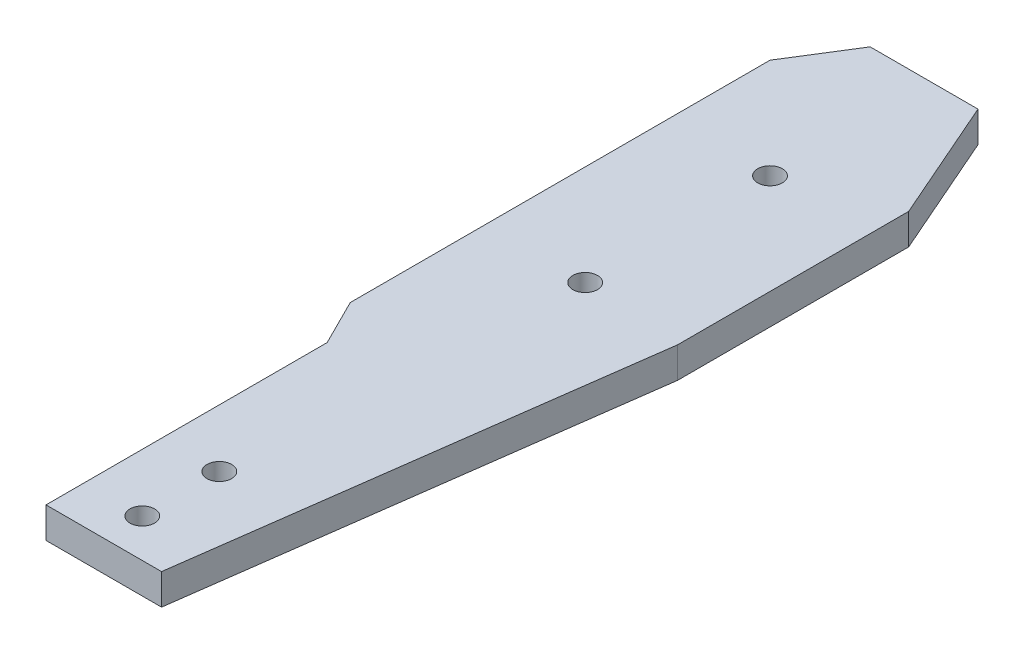
SolidWorks part; units mm, degrees
ref_plane "Front Plane" through (0, 0, 0) normal (0, 0, 1) x (1, 0, 0)
ref_plane "Top Plane" through (0, 0, 0) normal (0, 1, 0) x (1, 0, 0)
ref_plane "Right Plane" through (0, 0, 0) normal (1, 0, 0) x (0, 0, -1)
sketch "Sketch1" plane through (0, 0, 0) normal (0, 1, 0) x (1, 0, 0)
  line L1 (0, -54.5) -> (-3, -60.5)
  line L2 (-3, -60.5) -> (-3, -97)
  line L3 (-3, -97) -> (-18, -97)
  line L4 (-18, -97) -> (-26, -38)
  line L5 (-26, -38) -> (-26, -8)
  line L6 (-26, -8) -> (-19, 8)
  line L7 (-19, 8) -> (-5, 8)
  line L8 (-5, 8) -> (0, 0)
  line L10 (0, 0) -> (0, -54.5)
  line L11 (5, 8) -> (0, 0)
  line L12 (19, 8) -> (5, 8)
  line L13 (26, -8) -> (19, 8)
  line L14 (26, -38) -> (26, -8)
  line L15 (18, -97) -> (26, -38)
  line L16 (3, -97) -> (18, -97)
  line L17 (3, -60.5) -> (3, -97)
  line L18 (0, -54.5) -> (3, -60.5)
  dimension "D2" = 105
  dimension "D3" = 6
  dimension "D4" = 3
  dimension "D5" = 15
  dimension "D6" = 30
  dimension "D7" = 16
  dimension "D8" = 14
  dimension "D9" = 8
  dimension "D10" = 5
  dimension "D11" = 36.5
  dimension "D12" = 26
extrude "Boss-Extrude1" add sketch "Sketch1" along normal blind 4 contours L10 L18 L17 L16 L15 L14 L13 L12 L11
sketch "Sketch2" plane through (0, 4, 0) normal (0, 1, 0) x (1, 0, 0)
  line L4 (0, 0) -> (0, -54.5) construction
  line L5 (19, 8) -> (5, 8) construction
  line L6 (3, -60.5) -> (3, -97) construction
  line L7 (3, -97) -> (18, -97) construction
  circle A0 centre (13, -13) radius 1.6
  circle A1 centre (13, -37) radius 1.6
  circle A2 centre (10.5, -82) radius 1.6
  circle A3 centre (10.5, -92) radius 1.6
  dimension "D1" = 3.2
  dimension "D2" = 3.2
  dimension "D3" = 3.2
  dimension "D4" = 3.2
  dimension "D5" = 5
  dimension "D6" = 10
  dimension "D7" = 7.5
  dimension "D8" = 13
  dimension "D9" = 21
  dimension "D10" = 24
extrude "Cut-Extrude1" cut sketch "Sketch2" against normal through all
